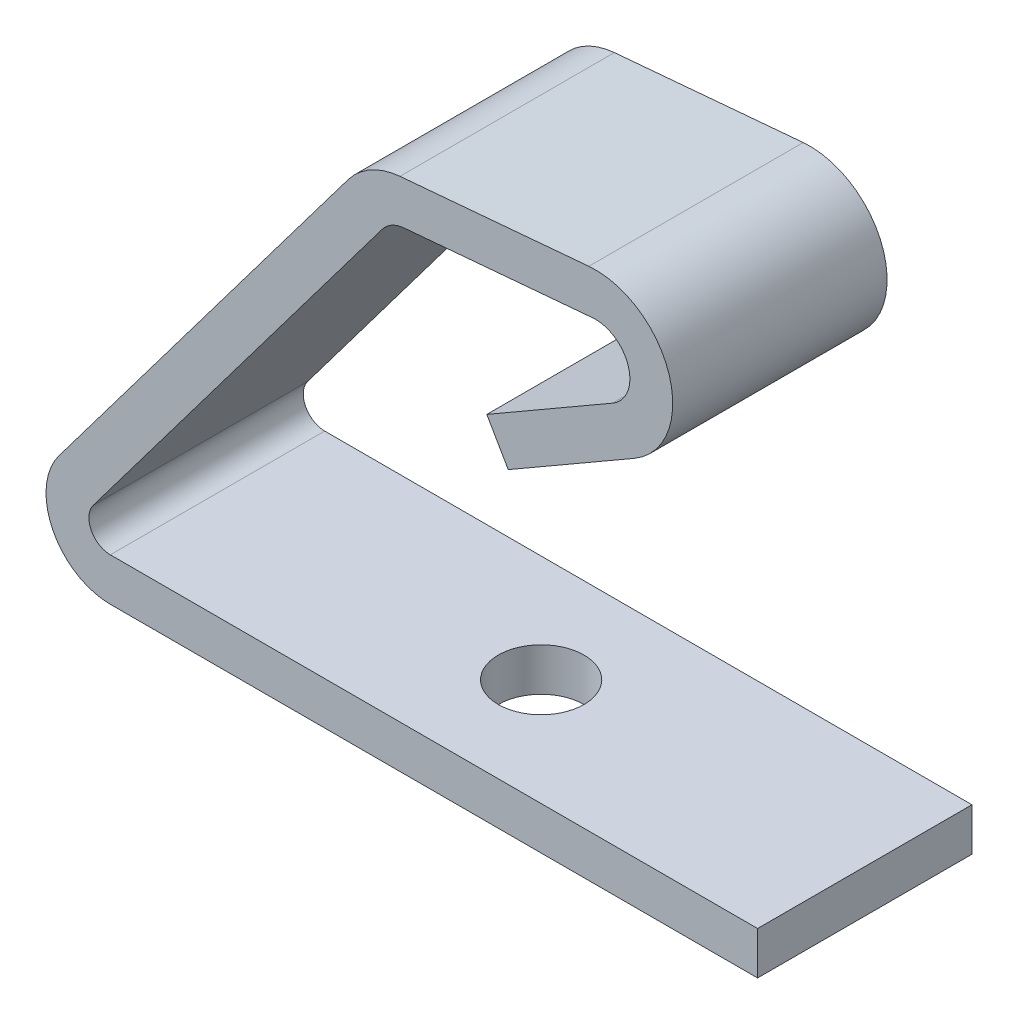
SolidWorks part; units mm, degrees
ref_plane "Front Plane" through (0, 0, 0) normal (0, 0, 1) x (1, 0, 0)
ref_plane "Top Plane" through (0, 0, 0) normal (0, 1, 0) x (1, 0, 0)
ref_plane "Right Plane" through (0, 0, 0) normal (1, 0, 0) x (0, 0, -1)
sketch "Sketch1" plane through (0, 0, 0) normal (0, 0, 1) x (1, 0, 0)
  line L0 (0, 0) -> (15, 0)
  line L1 (0, 0) -> (-0.0972, 0)
  line L2 (-0.4965, 0.8009) -> (6.248, 9.7511)
  line L3 (6.746, 10.0272) -> (11.1512, 10.4126)
  line L4 (11.6209, 8.9228) -> (8.6838, 7.2271)
  arc A0 (-0.0972, 0) -> (-0.4965, 0.8009) centre (-0.0972, 0.5) cw
  arc A1 (6.248, 9.7511) -> (6.746, 10.0272) centre (6.807, 9.3298) cw
  arc A2 (11.1512, 10.4126) -> (11.6209, 8.9228) centre (11.2209, 9.6156) cw
  point P9 (-1.1, 0)
  point P12 (6.4355, 10)
  point P15 (14.746, 10.7271)
  dimension "D6" = 0.5
  dimension "D7" = 0.7
  dimension "D11" = 0.8
  dimension "D1" = 53
  dimension "D2" = 132
  dimension "D3" = 10
  dimension "D4" = 1.1
  dimension "D5" = 15
  dimension "D8" = 8
  dimension "D9" = 25
  dimension "D10" = 7
extrude "Extrude-Thin2" add sketch "Sketch1" along normal blind 5 thin
sketch "Sketch2" plane through (0, 0, 0) normal (0, 1, 0) x (1, 0, 0)
  line L2 (15, -5) -> (-0.0972, -5) construction
  line L3 (15, -5) -> (15, 0) construction
  circle A0 centre (7.4514, -2.5) radius 1
  point P0 (0, 0)
  point P4 (7.4514, -5)
  point P8 (15, -2.5)
  dimension "D1" = 2
extrude "Cut-Extrude1" cut sketch "Sketch2" against normal up to next
